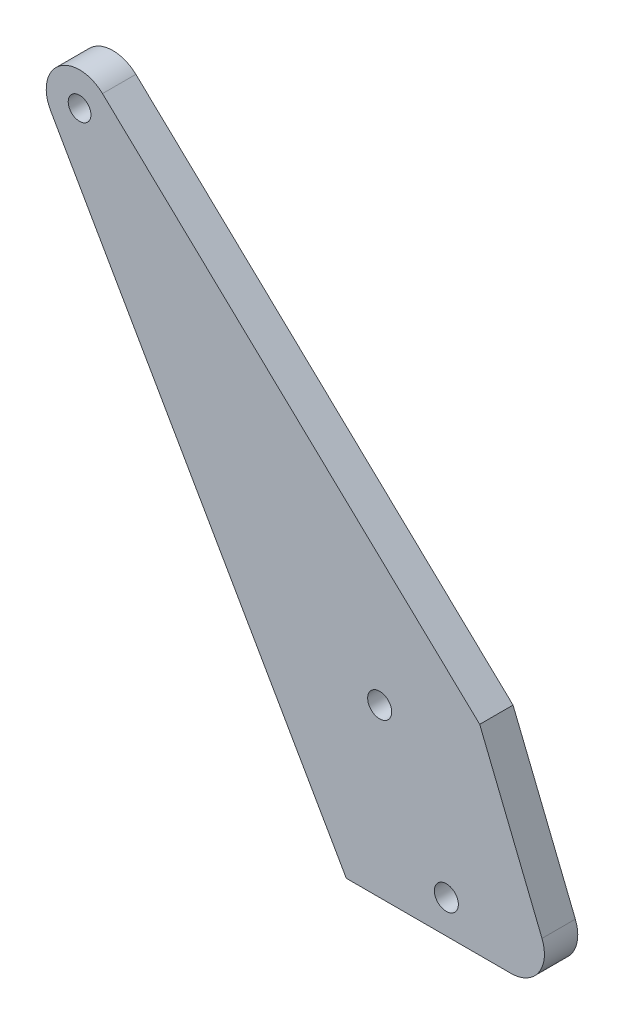
SolidWorks part; units mm, degrees
ref_plane "Front Plane" through (0, 0, 0) normal (0, 0, 1) x (1, 0, 0)
ref_plane "Top Plane" through (0, 0, 0) normal (0, 1, 0) x (1, 0, 0)
ref_plane "Right Plane" through (0, 0, 0) normal (1, 0, 0) x (0, 0, -1)
sketch "Sketch1" plane through (0, 0, 0) normal (0, 0, 1) x (1, 0, 0)
  line L1 (0, 0) -> (-25.4, 0)
  line L6 (-71.8309, 106.208) -> (0, 38.1)
  line L7 (-81.712, 98.4471) -> (-25.4, 0)
  line L8 (-323.85, -215.9) -> (44.45, -215.9) construction
  line L9 (0, 38.1) -> (15.3934, 0)
  line L10 (15.3934, 0) -> (0, 0)
  line L11 (0, 38.1) -> (0, 0) construction
  arc A1 (-71.8309, 106.208) -> (-81.712, 98.4471) centre (-76.2, 101.6) ccw
  circle A2 centre (-6.35, 6.35) radius 2.286
  circle A3 centre (-19.05, 31.75) radius 2.286
  circle A4 centre (-76.2, 101.6) radius 2.159
  dimension "D3" = 76.2
  dimension "D5" = 12.7
  dimension "D7" = 4.572
  dimension "D4" = 6.35
  dimension ".17" = 4.318
  dimension "D1" = 25.4
  dimension "D2" = 38.1
  dimension "D6" = 317.5
  dimension "D8" = 31.75
  dimension "D9" = 19.05
  dimension "D11" = 6.35
  dimension "D12" = 22
extrude "Boss-Extrude1" add sketch "Sketch1" against normal blind 6.35
fillet "Fillet1" radius 6.35 1 edges at (15.3934, 0, -3.175)
sketch "Sketch3" plane through (0, 0, 0) normal (0, 0, 1) x (1, 0, 0)
  line L0 (-76.2, 101.6) -> (-180.5328, -115.6414) construction
  line L1 (-13.2351, 71.3603) -> (-117.5679, -145.881)
  line L2 (-139.1649, 131.8397) -> (-243.4978, -85.4017)
  arc A0 (-13.2351, 71.3603) -> (-139.1649, 131.8397) centre (-76.2, 101.6) ccw
  arc A1 (-243.4978, -85.4017) -> (-117.5679, -145.881) centre (-180.5328, -115.6414) ccw
  point P4 (-128.3664, -7.0207)
  dimension "D1" = 139.7
